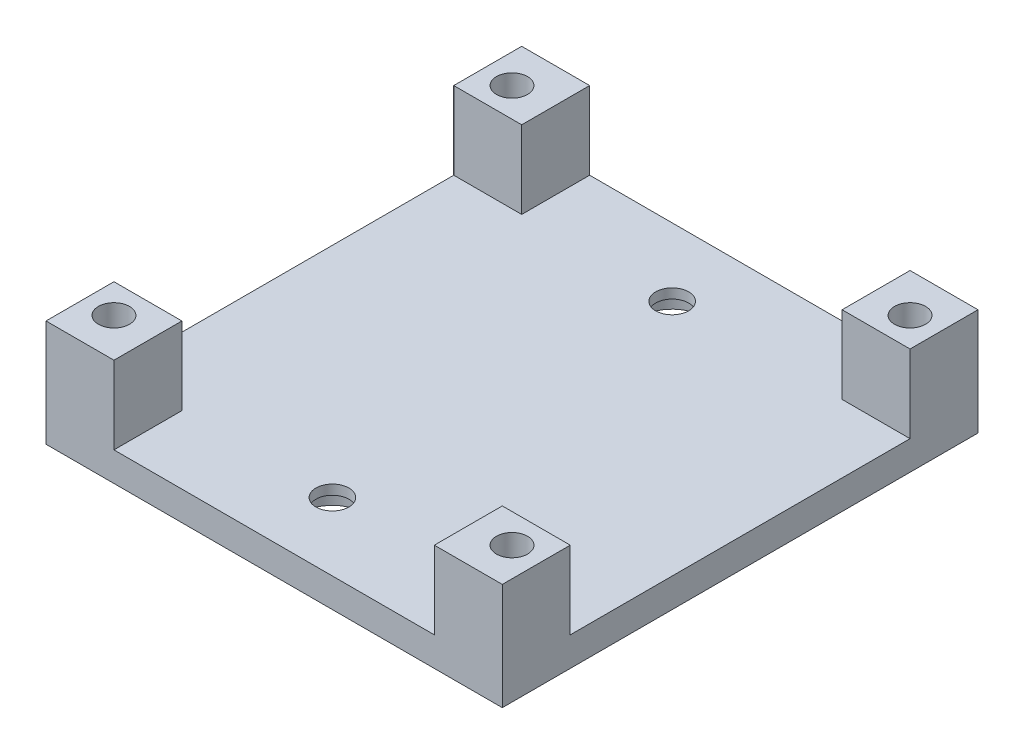
SolidWorks part; units mm, degrees
ref_plane "Alzado" through (0, 0, 0) normal (0, 0, 1) x (1, 0, 0)
ref_plane "Planta" through (0, 0, 0) normal (0, 1, 0) x (1, 0, 0)
ref_plane "Vista lateral" through (0, 0, 0) normal (1, 0, 0) x (0, 0, -1)
sketch "Croquis1" plane through (0, 0, 0) normal (0, 1, 0) x (1, 0, 0)
  line L1 (0, 0) -> (47, 0)
  line L2 (0, 0) -> (0, 49)
  line L3 (0, 49) -> (47, 49)
  line L4 (47, 0) -> (47, 49)
  dimension "D1" = 47
  dimension "D2" = 49
extrude "Saliente-Extruir1" add sketch "Croquis1" along normal blind 3
sketch "Croquis14" plane through (0, 3, 0) normal (0, 1, 0) x (1, 0, 0)
  line L0 (23.5, 49) -> (23.5, 0) construction
  line L1 (0, 49) -> (7, 49)
  line L2 (0, 49) -> (0, 42)
  line L3 (0, 42) -> (7, 42)
  line L4 (7, 49) -> (7, 42)
  line L5 (47, 49) -> (0, 49) construction
  line L6 (0, 0) -> (47, 0) construction
  line L7 (0, 24.5) -> (47, 24.5) construction
  line L8 (0, 49) -> (0, 0) construction
  line L9 (47, 0) -> (47, 49) construction
  line L10 (47, 49) -> (47, 42)
  line L11 (47, 49) -> (40, 49)
  line L12 (40, 49) -> (40, 42)
  line L13 (47, 42) -> (40, 42)
  line L14 (47, 0) -> (47, 7)
  line L15 (47, 0) -> (40, 0)
  line L16 (40, 0) -> (40, 7)
  line L17 (47, 7) -> (40, 7)
  line L18 (7, 0) -> (7, 7)
  line L19 (0, 7) -> (7, 7)
  line L20 (0, 0) -> (0, 7)
  line L21 (0, 0) -> (7, 0)
  dimension "D1" = 7
  dimension "D2" = 7
extrude "Saliente-Extruir4" add sketch "Croquis14" along normal blind 8
sketch "Croquis17" plane through (0, 0, 0) normal (0, -1, 0) x (1, 0, 0)
  line L0 (3, 0) -> (3, -49) construction
  line L1 (0, 0) -> (47, 0) construction
  line L2 (47, -49) -> (0, -49) construction
  line L3 (44, 0) -> (44, -49) construction
  line L4 (0, -4) -> (47, -4) construction
  line L5 (0, -49) -> (0, 0) construction
  line L6 (47, 0) -> (47, -49) construction
  line L7 (0, -45) -> (47, -45) construction
  dimension "D1" = 4
  dimension "D2" = 3
  dimension "D3" = 3
  dimension "D4" = 4
hole_wizard "Taladro de margen para M35" positions "Croquis3D7" profile "Croquis18" hole size "M3" standard "ISO" end condition up to next
sketch3d "Croquis3D7"
  line L0 (3, 0, 0) -> (3, 0, -49) construction
  line L1 (0, 0, -4) -> (47, 0, -4) construction
  line L2 (44, 0, 0) -> (44, 0, -49) construction
  line L3 (0, 0, -45) -> (47, 0, -45) construction
  point P0 (3, 0, -4)
  point P6 (44, 0, -4)
  point P10 (44, 0, -45)
  point P14 (3, 0, -45)
sketch "Croquis18" plane through (3, 0, -4) normal (1, 0, 0) x (0, 0, -1)
  line L0 (0, 0) -> (0, 11)
  line L1 (0, 11) -> (1.6, 11)
  line L2 (1.6, 11) -> (1.6, 0)
  line L5 (1.6, 0) -> (0, 0)
  line L11 (0, -6.35) -> (0, 107.95) construction
  dimension "Diámetro de taladro hasta el siguiente" = 3.2
  dimension "Profundidad de taladro hasta el siguiente" = 11
sketch "Croquis22" plane through (0, 0, 0) normal (0, -1, 0) x (1, 0, 0)
  line L0 (22.5, 0) -> (22.5, -49) construction
  line L3 (47, -7) -> (47, -42) construction
  line L4 (0, -49) -> (0, 0) construction
  line L5 (47, 0) -> (47, -49) construction
  line L6 (0, -24.5) -> (47, -24.5) construction
  line L7 (0, -7) -> (47, -7) construction
  line L8 (0, -42) -> (47, -42) construction
  line L9 (23.5, 0) -> (23.5, -49) construction
  line L10 (0, 0) -> (47, 0) construction
  dimension "D1" = 35
  dimension "D2" = 17.5
  dimension "D3" = 1
hole_wizard "Refrentado para tornillo con cabeza plana de M31" positions "Croquis3D11" profile "Croquis24" counterbore size "M3" standard "ISO" end condition through all
sketch3d "Croquis3D11"
  line L0 (0, 0, -7) -> (47, 0, -7) construction
  line L1 (0, 0, -42) -> (47, 0, -42) construction
  line L2 (22.5, 0, 0) -> (22.5, 0, -49) construction
  point P0 (22.5, 0, -7)
  point P4 (22.5, 0, -42)
  dimension "D1" = 0
  dimension "D2" = 0
sketch "Croquis24" plane through (22.5, 0, -7) normal (1, 0, 0) x (0, 0, -1)
  line L0 (0, 0) -> (0, 11)
  line L1 (0, 11) -> (1.7, 11)
  line L3 (1.7, 11) -> (1.7, 2)
  line L4 (1.7, 2) -> (3.25, 2)
  line L5 (3.25, 2) -> (3.25, 0)
  line L7 (3.25, 0) -> (0, 0)
  line L11 (0, -6.35) -> (0, 107.95) construction
  dimension "Diámetro de taladro hasta el siguiente" = 3.4
  dimension "Profundidad de taladro hasta el siguiente" = 11
  dimension "Diámetro de refrentado" = 6.5
  dimension "Profundidad de refrentado" = 2
sketch "Croquis25" plane through (0, 0, 0) normal (0, -1, 0) x (1, 0, 0)
  line L0 (0, -24.5) -> (47, -24.5) construction
  line L1 (0, -49) -> (0, 0) construction
  line L2 (47, 0) -> (47, -49) construction
  line L3 (23.5, 0) -> (23.5, -49) construction
  line L4 (0, 0) -> (47, 0) construction
  line L5 (47, -49) -> (0, -49) construction
  circle A0 centre (11.75, -12.25) radius 4.75
  circle A1 centre (35.25, -12.25) radius 4.75
  circle A2 centre (35.25, -36.75) radius 4.75
  circle A3 centre (11.75, -36.75) radius 4.75
  dimension "D1" = 9.5
  dimension "D2" = 12.25
  dimension "D3" = 11.75
extrude "Cortar-Extruir4" cut sketch "Croquis25" against normal blind 2.54
